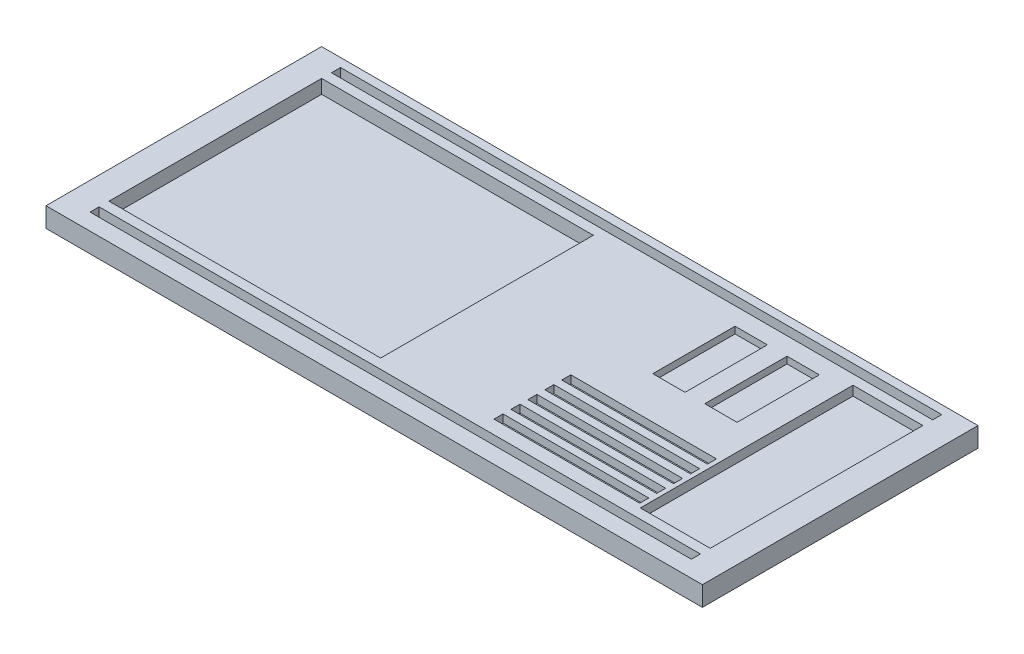
SolidWorks part; units mm, degrees
ref_plane "Front Plane" through (0, 0, 0) normal (0, 0, 1) x (1, 0, 0)
ref_plane "Top Plane" through (0, 0, 0) normal (0, 1, 0) x (1, 0, 0)
ref_plane "Right Plane" through (0, 0, 0) normal (1, 0, 0) x (0, 0, -1)
sketch "Sketch1" plane through (0, 0, 0) normal (0, 1, 0) x (1, 0, 0)
  line L1 (-83.35, 35) -> (83.35, 35)
  line L2 (-83.35, 35) -> (-83.35, -35)
  line L3 (-83.35, -35) -> (83.35, -35)
  line L4 (83.35, 35) -> (83.35, -35)
  line L5 (-83.35, 35) -> (83.35, -35) construction
  line L6 (-83.35, -35) -> (83.35, 35) construction
  point P0 (0, 0)
  dimension "D1" = 166.7
  dimension "D2" = 70
extrude "Boss-Extrude2" add sketch "Sketch1" along normal blind 5
sketch "Sketch2" plane through (0, 5, 0) normal (0, 1, 0) x (1, 0, 0)
  line L0 (-83.35, 35) -> (-83.35, -35) construction
  line L1 (-76.35, 28) -> (-7.35, 28)
  line L2 (-76.35, 28) -> (-76.35, -26)
  line L3 (-76.35, -26) -> (-7.35, -26)
  line L4 (-7.35, 28) -> (-7.35, -26)
  line L5 (83.35, 35) -> (-83.35, 35) construction
  dimension "D1" = 69
  dimension "D2" = 54
  dimension "D3" = 7
  dimension "D4" = 7
extrude "Cut-Extrude1" cut sketch "Sketch2" against normal blind 3.5
sketch "Sketch4" plane through (0, 5, 0) normal (0, 1, 0) x (1, 0, 0)
  line L0 (83.35, 35) -> (-83.35, 35) construction
  line L1 (43.85, 26.0048) -> (52.05, 26.0048)
  line L2 (43.85, 26.0048) -> (43.85, 5.1148)
  line L3 (43.85, 5.1148) -> (52.05, 5.1148)
  line L4 (52.05, 26.0048) -> (52.05, 5.1148)
  line L6 (30.65, 26) -> (38.85, 26)
  line L7 (30.65, 26) -> (30.65, 5.11)
  line L8 (30.65, 5.11) -> (38.85, 5.11)
  line L9 (38.85, 26) -> (38.85, 5.11)
  line L20 (-7.35, -26) -> (-7.35, 28) construction
  dimension "D1" = 9
  dimension "D2" = 5
  dimension "D3" = 38
  dimension "D4" = 20.89
  dimension "D5" = 8.2
  dimension "D6" = 20.89
  dimension "D7" = 8.2
extrude "Cut-Extrude3" cut sketch "Sketch4" against normal blind 1.7 contours L9 L6 L7 L8 | L2 L1 L4 L3
sketch "Sketch3" plane through (0, 5, 0) normal (0, 1, 0) x (1, 0, 0)
  line L1 (58.6, 28) -> (76.35, 28)
  line L2 (58.6, 28) -> (58.6, -26)
  line L3 (58.6, -26) -> (76.35, -26)
  line L4 (76.35, 28) -> (76.35, -26)
  line L7 (83.35, -35) -> (83.35, 35) construction
  line L8 (83.35, 35) -> (-83.35, 35) construction
  line L9 (-83.35, -35) -> (83.35, -35) construction
  dimension "D1" = 7
  dimension "D2" = 7
  dimension "D3" = 9
  dimension "D4" = 17.75
extrude "Cut-Extrude4" cut sketch "Sketch3" against normal blind 2.4
sketch "Sketch5" plane through (0, 5, 0) normal (0, 1, 0) x (1, 0, 0)
  line L1 (-76.35, -28.5) -> (76.35, -28.5)
  line L2 (-76.35, -28.5) -> (-76.35, -30.8)
  line L3 (-76.35, -30.8) -> (76.35, -30.8)
  line L4 (76.35, -28.5) -> (76.35, -30.8)
  line L7 (83.35, -35) -> (83.35, 35) construction
  line L8 (-76.35, -26) -> (-7.35, -26) construction
  line L9 (-76.35, 32.8) -> (76.35, 32.8)
  line L10 (-76.35, 32.8) -> (-76.35, 30.5)
  line L11 (-76.35, 30.5) -> (76.35, 30.5)
  line L12 (76.35, 32.8) -> (76.35, 30.5)
  line L13 (76.35, 28) -> (58.6, 28) construction
  dimension "D1" = 2.3
  dimension "D2" = 152.7
  dimension "D3" = 7
  dimension "D4" = 2.5
  dimension "D5" = 7
  dimension "D6" = 2.5
extrude "Cut-Extrude5" cut sketch "Sketch5" against normal blind 2.3 contours L2 L1 L4 L3 | L9 L12 L11 L10
sketch "Sketch6" plane through (0, 5, 0) normal (0, 1, 0) x (1, 0, 0)
  line L0 (58.6, 28) -> (58.6, -26) construction
  line L1 (58.6, 28) -> (58.6, -26) construction
  line L16 (57.4778, -7.8483) -> (57.4778, -5.5483)
  line L17 (20.4778, -5.5483) -> (57.4778, -5.5483)
  line L18 (20.4778, -7.8483) -> (20.4778, -5.5483)
  line L19 (20.4778, -7.8483) -> (57.4778, -7.8483)
  line L22 (20.4778, -9.8483) -> (57.4778, -9.8483)
  line L23 (20.4778, -9.8483) -> (20.4778, -12.1483)
  line L24 (20.4778, -12.1483) -> (57.4778, -12.1483)
  line L25 (57.4778, -9.8483) -> (57.4778, -12.1483)
  line L26 (57.4778, -16.4483) -> (57.4778, -14.1483)
  line L27 (20.4778, -14.1483) -> (57.4778, -14.1483)
  line L28 (20.4778, -16.4483) -> (20.4778, -14.1483)
  line L29 (20.4778, -16.4483) -> (57.4778, -16.4483)
  line L30 (20.4778, -18.4483) -> (57.4778, -18.4483)
  line L31 (20.4778, -18.4483) -> (20.4778, -20.7483)
  line L32 (20.4778, -20.7483) -> (57.4778, -20.7483)
  line L33 (57.4778, -18.4483) -> (57.4778, -20.7483)
  line L34 (57.4778, -25.0483) -> (57.4778, -22.7483)
  line L35 (20.4778, -22.7483) -> (57.4778, -22.7483)
  line L36 (20.4778, -25.0483) -> (20.4778, -22.7483)
  line L37 (20.4778, -25.0483) -> (57.4778, -25.0483)
  dimension "D1" = 1.1222
  dimension "D2" = 1.1222
  dimension "D3" = 1.1222
  dimension "D4" = 1.1222
  dimension "D5" = 1.1222
  dimension "D6" = 37
  dimension "D7" = 37
  dimension "D8" = 37
  dimension "D9" = 37
  dimension "D10" = 37
other "AlignGroup1"
extrude "Cut-Extrude7" cut sketch "Sketch6" against normal blind 2 contours L33 L30 L31 L32 | L28 L29 L26 L27 | L25 L22 L23 L24 | L18 L19 L16 L17 | L34 L35 L36 L37
